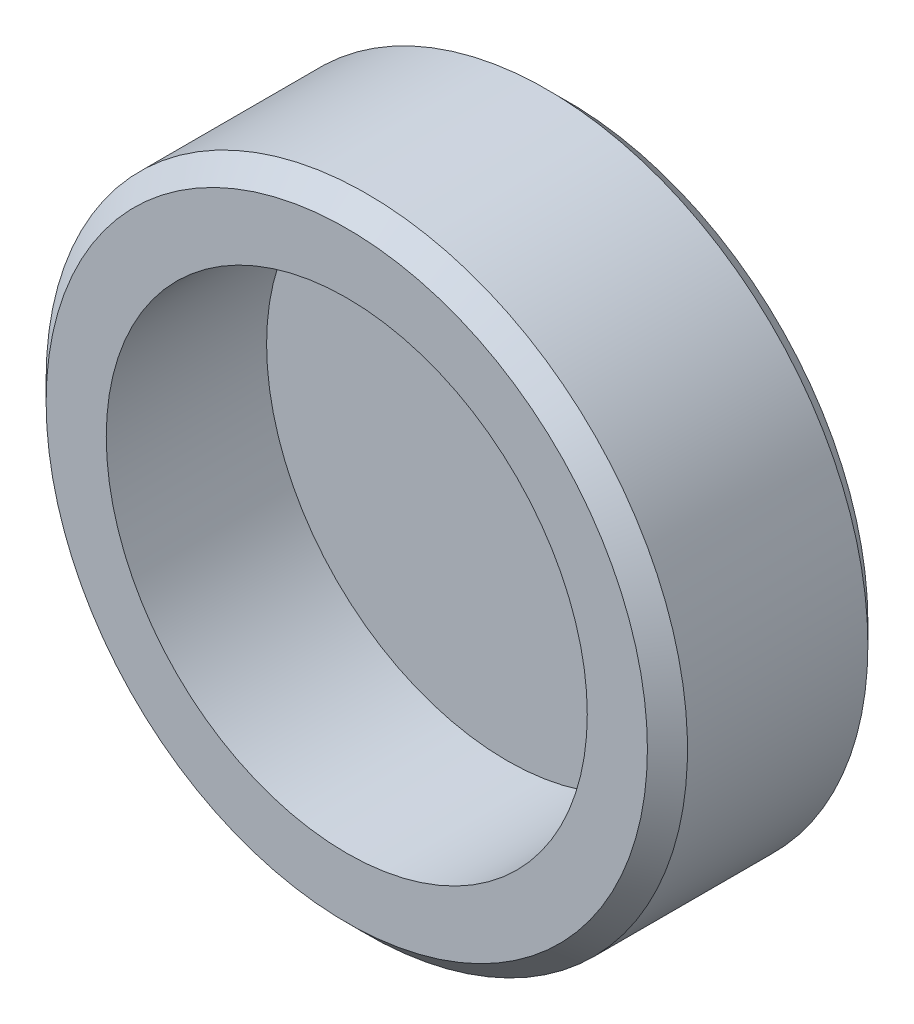
SolidWorks part; units mm, degrees
ref_plane "前视基准面" through (0, 0, 0) normal (0, 0, 1) x (1, 0, 0)
ref_plane "上视基准面" through (0, 0, 0) normal (0, 1, 0) x (1, 0, 0)
ref_plane "右视基准面" through (0, 0, 0) normal (1, 0, 0) x (0, 0, -1)
sketch "草图1" plane through (0, 0, 0) normal (0, 0, 1) x (1, 0, 0)
  circle A0 centre (0, 0) radius 16
  dimension "D1" = 32
extrude "拉伸1" add sketch "草图1" along normal blind 11
chamfer "倒角1" distance 1 angle 45 2 edges at (16, 0, 0) (16, 0, 11)
sketch "草图2" plane through (0, 0, 11) normal (0, 0, 1) x (1, 0, 0)
  circle A0 centre (0, 0) radius 12
  dimension "D1" = 24
extrude "切除-拉伸1" cut sketch "草图2" against normal blind 8
